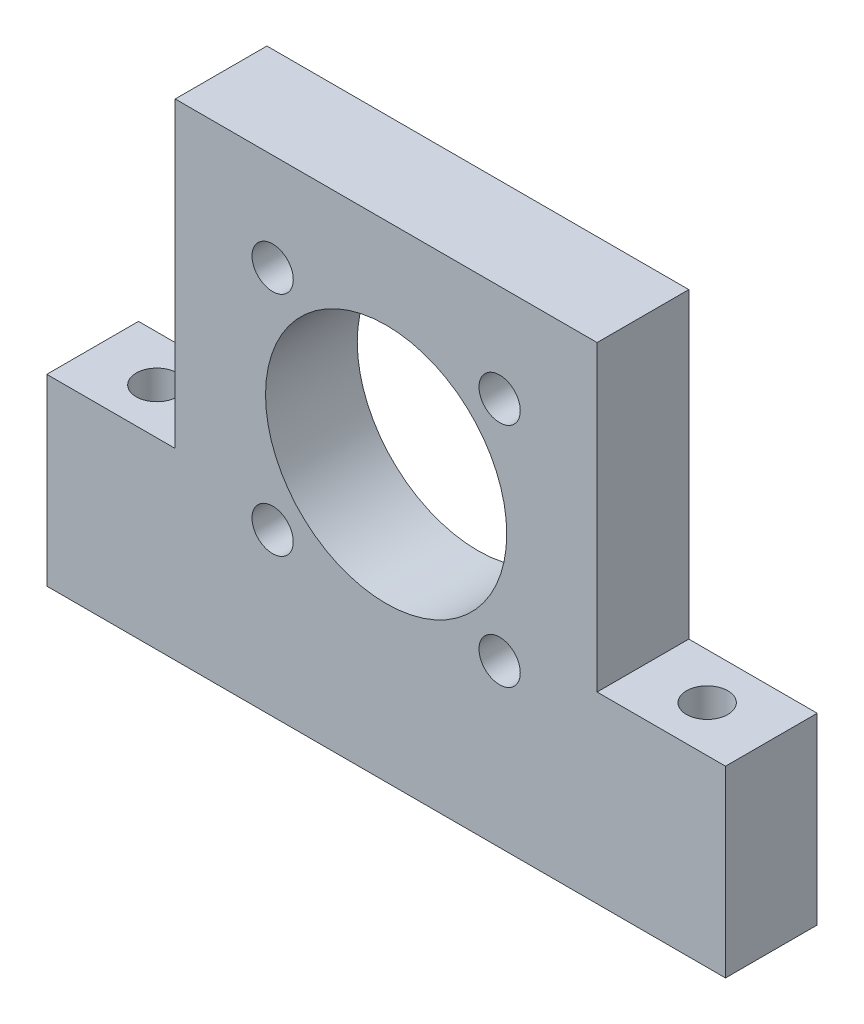
SolidWorks part; units mm, degrees
ref_plane "Plan de face" through (0, 0, 0) normal (0, 0, 1) x (1, 0, 0)
ref_plane "Plan de dessus" through (0, 0, 0) normal (0, 1, 0) x (1, 0, 0)
ref_plane "Plan de droite" through (0, 0, 0) normal (1, 0, 0) x (0, 0, -1)
sketch "Esquisse1" plane through (0, 0, 0) normal (0, 0, 1) x (1, 0, 0)
  line L0 (-23, 23) -> (23, 23)
  line L1 (-23, 23) -> (-23, -10)
  line L2 (23, 23) -> (23, -10)
  line L3 (23, -10) -> (37, -10)
  line L4 (-23, -10) -> (-37, -10)
  line L5 (-37, -10) -> (-37, -30)
  line L6 (37, -10) -> (37, -30)
  line L7 (-37, -30) -> (37, -30)
  circle A0 centre (0, 0) radius 13.15
  point P22 (22.5537, -22.1538)
  dimension "D7" = 26.3
  dimension "D1" = 46
  dimension "D2" = 74
  dimension "D4" = 14
  dimension "D5" = 33
  dimension "D6" = 20
  dimension "D9" = 23
  dimension "D10" = 30
extrude "Boss.-Extru.1" add sketch "Esquisse1" along normal blind 10
sketch "Esquisse5" plane through (0, -30, 0) normal (0, -1, 0) x (1, 0, 0)
  line L0 (-37, 10) -> (0, 10) construction
  line L1 (-37, 10) -> (37, 10) construction
  line L3 (0, 10) -> (0, 0) construction
  line L4 (-37, 0) -> (37, 0) construction
  line L5 (-37, 10) -> (-37, 0) construction
  circle A0 centre (-30, 5) radius 2.25
  circle A1 centre (30, 5) radius 2.25
  dimension "D1" = 7
  dimension "D2" = 4.5
  dimension "D3" = 5
extrude "Enlèv. mat.-Extru.2" cut sketch "Esquisse5" against normal up to next
sketch "Sketch1" plane through (0, 0, 10) normal (0, 0, 1) x (1, 0, 0)
  line L0 (12.3744, 12.3744) -> (0, 0) construction
  line L1 (0, 0) -> (0, 23) construction
  line L2 (23, 23) -> (-23, 23) construction
  circle A0 centre (12.3744, 12.3744) radius 2.25
  dimension "D1" = 4.5
  dimension "D2" = 45
  dimension "D3" = 17.5
extrude "Cut-Extrude1" cut sketch "Sketch1" against normal through all
pattern_circular "CirPattern1" count 4 over 360 about axis through (0, 0, 0) along (0, 0, 1) of "Cut-Extrude1"
